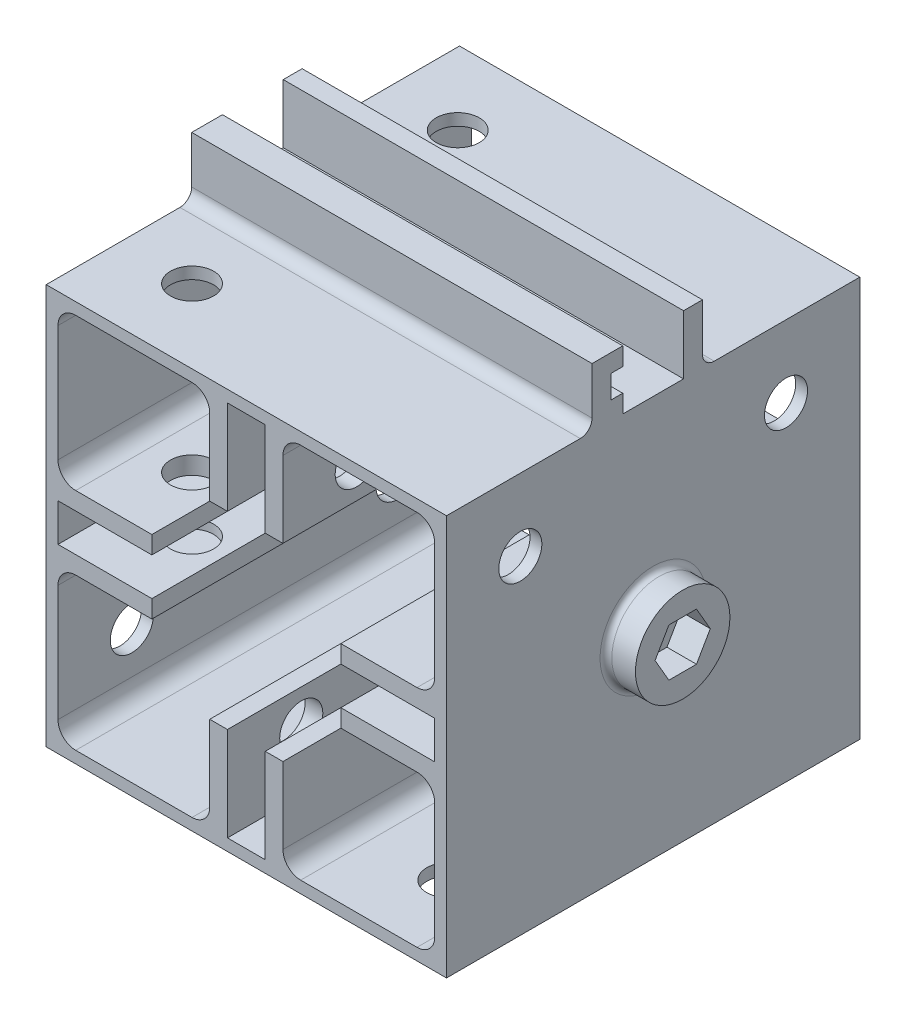
SolidWorks part; units mm, degrees
ref_plane "Front Plane" through (0, 0, 0) normal (0, 0, 1) x (1, 0, 0)
ref_plane "Top Plane" through (0, 0, 0) normal (0, 1, 0) x (1, 0, 0)
ref_plane "Right Plane" through (0, 0, 0) normal (1, 0, 0) x (0, 0, -1)
sketch "Sketch1" plane through (0, 0, 0) normal (0, 0, 1) x (1, 0, 0)
  line L0 (12.7, -12.7) -> (12.7, 12.7)
  line L1 (12.7, 12.7) -> (-12.7, 12.7)
  line L2 (-12.7, 12.7) -> (-12.7, -12.7)
  line L3 (-12.7, -12.7) -> (12.7, -12.7)
  line L4 (12.5, -12.5) -> (12.5, 12.5) construction
  line L5 (12.5, 12.5) -> (-12.5, 12.5) construction
  line L6 (-12.5, 12.5) -> (-12.5, -12.5) construction
  line L7 (-12.5, -12.5) -> (12.5, -12.5) construction
  line L8 (31.7, -31.7) -> (31.7, 31.7)
  line L9 (31.7, 31.7) -> (-31.7, 31.7)
  line L10 (-31.7, 31.7) -> (-31.7, -31.7)
  line L11 (-31.7, -31.7) -> (31.7, -31.7)
  line L12 (31.9, -31.9) -> (31.9, 31.9)
  line L13 (31.9, 31.9) -> (-31.9, 31.9)
  line L14 (-31.9, 31.9) -> (-31.9, -31.9)
  line L15 (-31.9, -31.9) -> (31.9, -31.9)
  line L16 (33.9, -33.9) -> (33.9, 33.9)
  line L17 (33.9, 33.9) -> (-33.9, 33.9)
  line L18 (-33.9, 33.9) -> (-33.9, -33.9)
  line L19 (-33.9, -33.9) -> (33.9, -33.9)
  line L20 (0, -33.9) -> (0, 33.9) construction
  line L21 (-33.9, 0) -> (33.9, 0) construction
  line L22 (3.2, -33.9) -> (3.2, -31.9)
  line L23 (-33.9, -3.2) -> (-31.9, -3.2)
  line L24 (-3.2, -33.9) -> (-3.2, -31.9)
  line L25 (-33.9, 3.2) -> (-31.9, 3.2)
  line L26 (-33.9, 6.2) -> (-31.9, 6.2)
  line L27 (-6.2, -33.9) -> (-6.2, -31.9)
  line L28 (-33.9, -6.2) -> (-31.9, -6.2)
  line L29 (6.2, -33.9) -> (6.2, -31.9)
  line L30 (-6.2, -12.5) -> (-6.2, 12.5)
  line L31 (-3.2, -12.5) -> (-3.2, 12.5)
  line L32 (3.2, -12.5) -> (3.2, 12.5)
  line L33 (6.2, -12.5) -> (6.2, 12.5)
  line L34 (-6.2, -31.7) -> (-6.2, -12.7)
  line L35 (-3.2, -31.7) -> (-3.2, -12.7)
  line L36 (3.2, -31.7) -> (3.2, -12.7)
  line L37 (6.2, -31.7) -> (6.2, -12.7)
  line L38 (31.9, -6.2) -> (33.9, -6.2)
  line L39 (31.9, -3.2) -> (33.9, -3.2)
  line L40 (31.9, 6.2) -> (33.9, 6.2)
  line L41 (31.9, 3.2) -> (33.9, 3.2)
  line L42 (12.7, -6.2) -> (31.7, -6.2)
  line L43 (12.7, -3.2) -> (31.7, -3.2)
  line L44 (12.7, 3.2) -> (31.7, 3.2)
  line L45 (12.7, 6.2) -> (31.7, 6.2)
  line L46 (3.2, 12.7) -> (3.2, 31.7)
  line L47 (6.2, 12.7) -> (6.2, 31.7)
  line L48 (-6.2, 12.7) -> (-6.2, 31.7)
  line L49 (-3.2, 12.7) -> (-3.2, 31.7)
  line L50 (6.2, 31.9) -> (6.2, 33.9)
  line L51 (3.2, 31.9) -> (3.2, 33.9)
  line L52 (-3.2, 31.9) -> (-3.2, 33.9)
  line L53 (-6.2, 31.9) -> (-6.2, 33.9)
  line L54 (-31.7, 3.2) -> (-12.7, 3.2)
  line L55 (-31.7, 6.2) -> (-12.7, 6.2)
  line L56 (-31.7, -6.2) -> (-12.7, -6.2)
  line L57 (-31.7, -3.2) -> (-12.7, -3.2)
  line L58 (-12.5, -6.2) -> (12.5, -6.2)
  line L59 (-12.5, -3.2) -> (12.5, -3.2)
  line L60 (-12.5, 3.2) -> (12.5, 3.2)
  line L61 (-12.5, 6.2) -> (12.5, 6.2)
  point P24 (0, 0)
  point P27 (0, 0)
sketch "Sketch2" plane through (0, 0, 0) normal (0, 0, 1) x (1, 0, 0)
  line L1 (3.2, 16) -> (6.2, 16)
  line L2 (-16, 3.2) -> (-16, 6.2)
  line L3 (21.7, 21.7) -> (-21.7, 21.7) construction
  line L4 (-31.7, 6.2) -> (-12.7, 6.2) construction
  line L5 (-31.7, 3.2) -> (-12.7, 3.2) construction
  line L6 (-31.7, -3.2) -> (-12.7, -3.2) construction
  line L7 (-31.7, -6.2) -> (-12.7, -6.2) construction
  line L8 (-6.2, -31.7) -> (-6.2, -12.7) construction
  line L9 (-3.2, -31.7) -> (-3.2, -12.7) construction
  line L10 (3.2, -31.7) -> (3.2, -12.7) construction
  line L11 (6.2, -31.7) -> (6.2, -12.7) construction
  line L12 (12.7, -6.2) -> (31.7, -6.2) construction
  line L13 (12.7, -3.2) -> (31.7, -3.2) construction
  line L14 (12.7, 3.2) -> (31.7, 3.2) construction
  line L15 (12.7, 6.2) -> (31.7, 6.2) construction
  line L16 (6.2, 12.7) -> (6.2, 31.7) construction
  line L17 (3.2, 12.7) -> (3.2, 31.7) construction
  line L18 (-3.2, 12.7) -> (-3.2, 31.7) construction
  line L19 (-6.2, 12.7) -> (-6.2, 31.7) construction
  line L20 (-33.9, 33.9) -> (-33.9, -33.9) construction
  line L21 (-33.9, -33.9) -> (33.9, -33.9) construction
  line L22 (33.9, -33.9) -> (33.9, 33.9) construction
  line L23 (33.9, 33.9) -> (-33.9, 33.9) construction
  line L24 (-31.9, 31.9) -> (-31.9, -31.9) construction
  line L25 (-31.9, -31.9) -> (31.9, -31.9) construction
  line L26 (31.9, -31.9) -> (31.9, 31.9) construction
  line L27 (31.9, 31.9) -> (-31.9, 31.9) construction
  line L32 (-31.9, 6.2) -> (-16, 6.2)
  line L33 (-31.9, 3.2) -> (-16, 3.2)
  line L34 (-31.9, -3.2) -> (-16, -3.2)
  line L35 (-31.9, -6.2) -> (-16, -6.2)
  line L36 (-6.2, -31.9) -> (-6.2, -16)
  line L37 (-3.2, -31.9) -> (-3.2, -16)
  line L38 (3.2, -31.9) -> (3.2, -16)
  line L39 (6.2, -31.9) -> (6.2, -16)
  line L40 (16, -6.2) -> (31.9, -6.2)
  line L41 (16, -3.2) -> (31.9, -3.2)
  line L42 (16, 3.2) -> (31.9, 3.2)
  line L43 (16, 6.2) -> (31.9, 6.2)
  line L44 (6.2, 16) -> (6.2, 31.9)
  line L45 (3.2, 16) -> (3.2, 31.9)
  line L46 (-3.2, 16) -> (-3.2, 31.9)
  line L47 (-6.2, 16) -> (-6.2, 31.9)
  line L48 (-33.9, 33.9) -> (-33.9, -33.9)
  line L49 (-33.9, -33.9) -> (33.9, -33.9)
  line L50 (33.9, -33.9) -> (33.9, 33.9)
  line L51 (33.9, 33.9) -> (-33.9, 33.9)
  line L52 (-31.9, 31.9) -> (-31.9, 6.2)
  line L53 (-31.9, -31.9) -> (-6.2, -31.9)
  line L54 (31.9, -31.9) -> (31.9, -6.2)
  line L55 (31.9, 31.9) -> (6.2, 31.9)
  line L56 (-33.9, 0) -> (33.9, 0) construction
  line L57 (-31.9, 0) -> (-12.7, 0) construction
  line L58 (0, -33.9) -> (0, 33.9) construction
  line L59 (0, -31.9) -> (0, -12.7) construction
  line L60 (12.7, 0) -> (31.9, 0) construction
  line L61 (0, 12.7) -> (0, 31.9) construction
  line L66 (-31.9, 3.2) -> (-31.9, -3.2)
  line L67 (-31.9, -6.2) -> (-31.9, -31.9)
  line L68 (-3.2, -31.9) -> (3.2, -31.9)
  line L69 (6.2, -31.9) -> (31.9, -31.9)
  line L70 (31.9, 6.2) -> (31.9, 31.9)
  line L71 (31.9, -3.2) -> (31.9, 3.2)
  line L72 (-6.2, 31.9) -> (-31.9, 31.9)
  line L73 (3.2, 31.9) -> (-3.2, 31.9)
  line L74 (3.2, -16) -> (6.2, -16)
  line L75 (-6.2, -16) -> (-3.2, -16)
  line L76 (-16, -6.2) -> (-16, -3.2)
  line L77 (-6.2, 16) -> (-3.2, 16)
  line L78 (16, -6.2) -> (16, -3.2)
  line L79 (16, 3.2) -> (16, 6.2)
  line L80 (21.7, 21.7) -> (21.7, -21.7) construction
  line L81 (21.7, -21.7) -> (-21.7, -21.7) construction
  line L82 (-21.7, 21.7) -> (-21.7, -21.7) construction
  line L83 (21.7, 21.7) -> (-21.7, -21.7) construction
  line L84 (21.7, -21.7) -> (-21.7, 21.7) construction
  point P0 (0, 0)
  point P72 (0, 0)
  point P91 (-22.3, 0)
  point P92 (-21.7, 0)
  point P93 (21.7, 0)
  point P94 (0, -21.7)
  point P95 (0, 21.7)
  point P96 (-16, -4.7)
  point P97 (-4.7, 16)
  point P98 (16, 4.7)
  point P99 (4.7, -16)
  dimension "D1" = 0.6
extrude "Boss-Extrude1" add sketch "Sketch2" along normal mid plane 70
fillet "Fillet1" radius 3 12 edges at (6.2, -31.9, 0) (-6.2, -31.9, 0) (31.9, 6.2, 0) (31.9, -6.2, 0) (-6.2, 31.9, 0) (6.2, 31.9, 0) (-31.9, -6.2, 0) (-31.9, 6.2, 0) (-31.9, -31.9, 0) (31.9, -31.9, 0) (31.9, 31.9, 0) (-31.9, 31.9, 0)
sketch "Sketch3" plane through (0, 33.9, 0) normal (0, 1, 0) x (1, 0, 0)
  line L0 (-21.7, 22.5) -> (-21.7, -22.5) construction
  circle A0 centre (-21.7, -22.5) radius 3.45 construction
  circle A1 centre (-21.7, -22.5) radius 3.65
  circle A2 centre (-21.7, -22.5) radius 9.5 construction
  circle A3 centre (-21.7, 0) radius 4.5 construction
  circle A4 centre (-21.7, 22.5) radius 3.45 construction
  circle A5 centre (-21.7, 22.5) radius 3.65
  circle A6 centre (-21.7, 22.5) radius 9.5 construction
  point P9 (-21.7, 0)
  dimension "D1" = 6.9
  dimension "D4" = 19
  dimension "D5" = 9
  dimension "D6" = 6.9
  dimension "D8" = 19
  dimension "D3" = 45
  dimension "D2" = 0.2
  dimension "D7" = 0.2
extrude "Cut-Extrude1" cut sketch "Sketch3" against normal up to vertex (38.6 mm away) up to point (-16, -4.7, 0)
sketch "Sketch4" plane through (33.9, 0, 0) normal (1, 0, 0) x (0, 0, -1)
  line L0 (-22.5, 21.7) -> (22.5, 21.7) construction
  circle A0 centre (-22.5, 21.7) radius 9.5 construction
  circle A1 centre (22.5, 21.7) radius 9.5 construction
  circle A2 centre (-22.5, 21.7) radius 3.45 construction
  circle A3 centre (22.5, 21.7) radius 3.45 construction
  circle A4 centre (0, 21.7) radius 4.5 construction
  circle A5 centre (22.5, 21.7) radius 3.65
  circle A6 centre (-22.5, 21.7) radius 3.65
  point P4 (0, 21.7)
  dimension "D2" = 9
  dimension "D3" = 19
  dimension "D4" = 6.9
  dimension "D1" = 45
  dimension "D5" = 0.2
extrude "Cut-Extrude2" cut sketch "Sketch4" against normal up to vertex (38.6 mm away) up to point (-4.7, 16, 0)
sketch "Sketch5" plane through (0, -33.9, 0) normal (0, -1, 0) x (1, 0, 0)
  line L0 (21.7, 22.5) -> (21.7, -22.5) construction
  circle A0 centre (21.7, 22.5) radius 3.45 construction
  circle A1 centre (21.7, -22.5) radius 3.45 construction
  circle A2 centre (21.7, 0) radius 4.5 construction
  circle A3 centre (21.7, 22.5) radius 9.5 construction
  circle A4 centre (21.7, -22.5) radius 9.5 construction
  circle A5 centre (21.7, -22.5) radius 3.65
  circle A6 centre (21.7, 22.5) radius 3.65
  point P4 (21.7, 0)
  dimension "D2" = 9
  dimension "D3" = 19
  dimension "D4" = 6.9
  dimension "D1" = 45
  dimension "D5" = 0.2
extrude "Cut-Extrude3" cut sketch "Sketch5" against normal up to vertex (38.6 mm away) up to point (16, 4.7, 0)
sketch "Sketch6" plane through (-33.9, 0, 0) normal (-1, 0, 0) x (0, 0, 1)
  line L0 (-22.5, -21.7) -> (22.5, -21.7) construction
  circle A0 centre (22.5, -21.7) radius 3.45 construction
  circle A1 centre (22.5, -21.7) radius 9.5 construction
  circle A2 centre (-22.5, -21.7) radius 9.5 construction
  circle A3 centre (-22.5, -21.7) radius 3.45 construction
  circle A4 centre (0, -21.7) radius 4.5 construction
  circle A5 centre (-22.5, -21.7) radius 3.65
  circle A6 centre (22.5, -21.7) radius 3.65
  point P4 (0, -21.7)
  dimension "D2" = 19
  dimension "D3" = 6.9
  dimension "D4" = 9
  dimension "D1" = 45
  dimension "D5" = 0.2
extrude "Cut-Extrude4" cut sketch "Sketch6" against normal up to vertex (38.6 mm away) up to point (4.7, -16, 0)
sketch "Sketch7" plane through (33.9, 0, 0) normal (1, 0, 0) x (0, 0, -1)
  line L0 (-35, 0) -> (35, 0) construction
  line L1 (-35, -33.9) -> (-35, 33.9) construction
  line L2 (35, -33.9) -> (35, 33.9) construction
  line L4 (2.3375, 4.0487) -> (-2.3375, 4.0487)
  line L5 (-2.3375, 4.0487) -> (-4.675, 0)
  line L6 (-4.675, 0) -> (-2.3375, -4.0487)
  line L7 (-2.3375, -4.0487) -> (2.3375, -4.0487)
  line L8 (2.3375, -4.0487) -> (4.675, 0)
  line L9 (4.675, 0) -> (2.3375, 4.0487)
  circle A0 centre (0, 0) radius 4.675 construction
  circle A1 centre (0, 0) radius 4.0487 construction
  circle A2 centre (0, 0) radius 2.675 construction
  circle A3 centre (0, 0) radius 8
  dimension "D1" = 9.35
  dimension "D2" = 5.35
  dimension "D3" = 16
extrude "Boss-Extrude2" add sketch "Sketch7" along normal blind 5
sketch "Sketch8" plane through (33.9, 0, 0) normal (1, 0, 0) x (0, 0, -1)
  circle A0 centre (0, 0) radius 2.675
  circle A1 centre (0, 0) radius 2.675 construction
extrude "Cut-Extrude5" cut sketch "Sketch8" against normal up to surface (17.9 mm away) up to face at (16, 4.7, 0)
fillet "Fillet2" radius 1 1 edges at (33.9, 0, 8)
sketch "Sketch9" plane through (33.9, 0, 0) normal (1, 0, 0) x (0, 0, -1)
  line L0 (-35, 33.9) -> (35, 33.9) construction
  line L1 (-4.95, 33.9) -> (4.95, 33.9) construction
  line L2 (-4.95, 33.9) -> (-4.95, 37.15) construction
  line L3 (-4.95, 43.9) -> (4.95, 43.9) construction
  line L4 (4.95, 33.9) -> (4.95, 43.9) construction
  line L5 (-4.95, 40.65) -> (-4.95, 43.9) construction
  line L6 (-4.95, 37.15) -> (-6.95, 37.15) construction
  line L8 (-4.95, 40.65) -> (-6.95, 40.65) construction
  line L9 (-6.95, 37.15) -> (-6.95, 40.65) construction
  line L10 (-4.95, 38.9) -> (-6.95, 40.65) construction
  line L11 (-4.95, 38.9) -> (-6.95, 37.15) construction
  line L13 (5.15, 33.9) -> (5.15, 43.9)
  line L15 (-5.15, 40.85) -> (-5.15, 43.9)
  line L16 (-5.15, 40.85) -> (-7.15, 40.85)
  line L17 (-7.15, 36.95) -> (-7.15, 40.85)
  line L18 (-5.15, 36.95) -> (-7.15, 36.95)
  line L19 (-5.15, 33.9) -> (-5.15, 36.95)
  line L20 (-5.15, 44.1) -> (5.15, 44.1) construction
  line L21 (8.35, 31.9) -> (8.35, 43.9)
  line L23 (-8.35, 31.9) -> (-8.35, 33.9)
  line L25 (-10.35, 33.9) -> (-10.35, 43.9)
  line L26 (-5.15, 43.9) -> (-10.35, 43.9)
  line L27 (5.15, 43.9) -> (8.35, 43.9)
  line L28 (-8.35, 44.05) -> (-10.35, 44.05) construction
  line L29 (-8.35, 44.05) -> (-8.35, 44.1) construction
  line L30 (5.15, 33.7) -> (5.15, 44.1) construction
  line L31 (8.35, 30.5) -> (8.35, 44.1) construction
  line L32 (-10.35, 33.75) -> (-10.35, 44.05) construction
  line L33 (-5.15, 40.85) -> (-5.15, 44.1) construction
  line L34 (-8.35, 31.9) -> (8.35, 31.9)
  line L35 (-8.35, 30.5) -> (-8.35, 33.75) construction
  line L36 (-10.35, 33.9) -> (-8.35, 33.9)
  line L37 (-8.35, 30.5) -> (8.35, 30.5) construction
  line L38 (-5.15, 33.7) -> (5.15, 33.7) construction
  line L39 (-5.15, 33.7) -> (-5.15, 36.95) construction
  line L40 (-8.35, 33.75) -> (-10.35, 33.75) construction
  line L41 (-5.15, 33.9) -> (5.15, 33.9)
  point P7 (0, 43.9)
  point P8 (-4.95, 38.9)
  point P16 (4.95, 38.9)
  dimension "D1" = 10
  dimension "D2" = 9.9
  dimension "D3" = 3.5
  dimension "D4" = 2
  dimension "D7" = 2
  dimension "D5" = 0.2
  dimension "D6" = 3.2
extrude "Boss-Extrude3" add sketch "Sketch9" against normal up to surface (67.8 mm away) up to face at (-33.9, -25.35, -22.5)
fillet "Fillet3" radius 2 2 edges at (0, 33.9, -8.35) (0, 33.9, 10.35)
sketch "Sketch10" plane through (38.9, 0, 0) normal (1, 0, 0) x (0, 0, -1)
  line L0 (-2.3375, 4.0487) -> (-4.675, 0) construction
  line L1 (-4.675, 0) -> (-2.3375, -4.0487) construction
  line L2 (-2.3375, -4.0487) -> (2.3375, -4.0487) construction
  line L3 (2.3375, -4.0487) -> (4.675, 0) construction
  line L4 (4.675, 0) -> (2.3375, 4.0487) construction
  line L5 (2.3375, 4.0487) -> (-2.3375, 4.0487) construction
  line L6 (-2.3375, 4.0487) -> (-4.675, 0)
  line L7 (-4.675, 0) -> (-2.3375, -4.0487)
  line L8 (-2.3375, -4.0487) -> (2.3375, -4.0487)
  line L9 (2.3375, -4.0487) -> (4.675, 0)
  line L10 (4.675, 0) -> (2.3375, 4.0487)
  line L11 (2.3375, 4.0487) -> (-2.3375, 4.0487)
  circle A0 centre (0, 0) radius 2.675 construction
  circle A1 centre (0, 0) radius 8
  circle A2 centre (0, 0) radius 8
  circle A3 centre (0, 0) radius 2.675
  dimension "D1" = 0
